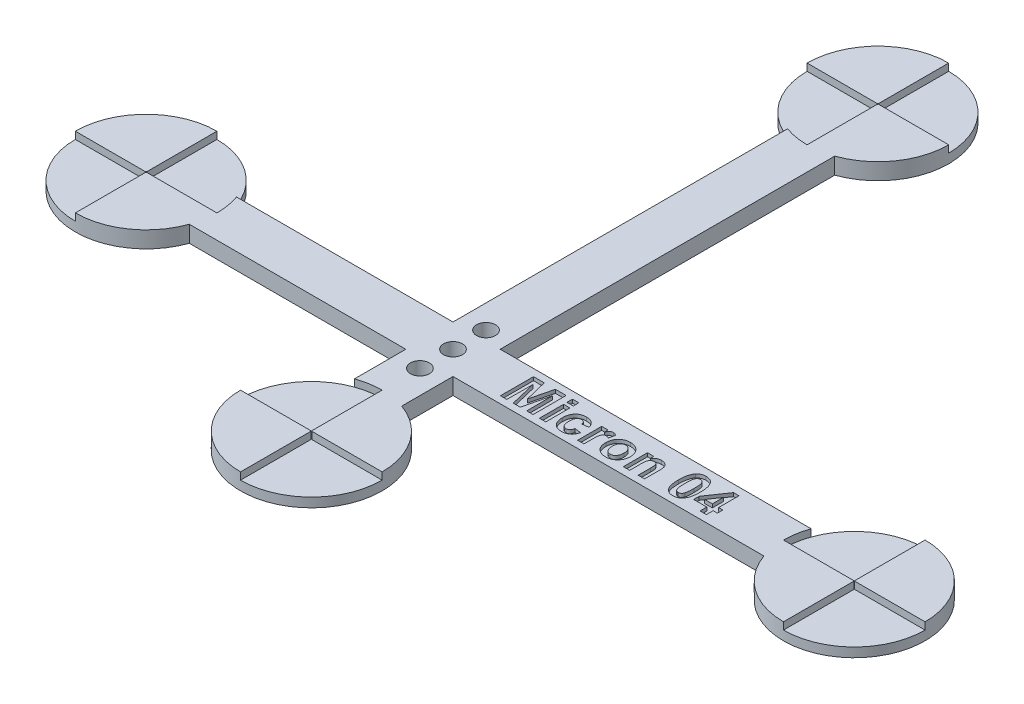
SolidWorks part; units mm, degrees
ref_plane "Front Plane" through (0, 0, 0) normal (0, 0, 1) x (1, 0, 0)
ref_plane "Top Plane" through (0, 0, 0) normal (0, 1, 0) x (1, 0, 0)
ref_plane "Right Plane" through (0, 0, 0) normal (1, 0, 0) x (0, 0, -1)
sketch "Sketch1" plane through (0, 0, 0) normal (0, 1, 0) x (1, 0, 0)
  line L0 (0, 0) -> (150, 0) construction
  line L1 (65, 90) -> (65, -30) construction
  line L2 (60, 75.8579) -> (60, 5)
  line L3 (70, 75.8579) -> (70, 5)
  line L4 (14.1421, 5) -> (60, 5)
  line L5 (14.1421, -5) -> (60, -5)
  line L6 (70, 5) -> (135.8579, 5)
  line L7 (60, -5) -> (60, -15.8579)
  line L8 (70, -5) -> (135.8579, -5)
  line L9 (70, -5) -> (70, -15.8579)
  arc A0 (14.1421, 5) -> (14.1421, -5) centre (0, 0) ccw
  arc A1 (135.8579, -5) -> (135.8579, 5) centre (150, 0) ccw
  arc A2 (70, 75.8579) -> (60, 75.8579) centre (65, 90) ccw
  arc A3 (60, -15.8579) -> (70, -15.8579) centre (65, -30) ccw
  point P15 (0, 0)
  point P16 (0, 0)
  point P19 (0, 0)
  point P20 (0, 0)
  dimension "D1" = 30
  dimension "D3" = 30
  dimension "D5" = 30
  dimension "D6" = 30
  dimension "D2" = 150
  dimension "D4" = 65
  dimension "D7" = 90
  dimension "D8" = 120
  dimension "D9" = 5
  dimension "D10" = 5
  dimension "D11" = 5
  dimension "D12" = 5
extrude "Boss-Extrude1" add sketch "Sketch1" along normal blind 3.5
sketch "Sketch2" plane through (0, 3.5, 0) normal (0, 1, 0) x (1, 0, 0)
  line L0 (65, -45) -> (65, -30.1)
  line L1 (-15, 0) -> (-0.1, 0)
  line L2 (50, 90) -> (64.9, 90)
  line L3 (0, 15) -> (0, 0.1)
  line L4 (150, 15) -> (150, 0.1)
  line L5 (50, -30) -> (64.9, -30)
  line L6 (65.1, 90) -> (80, 90)
  line L7 (65, 90.1) -> (65, 105)
  line L8 (65, 75) -> (65, 89.9)
  line L9 (65, -29.9) -> (65, -15)
  line L10 (65.1, -30) -> (80, -30)
  line L11 (135, 0) -> (149.9, 0)
  line L12 (0.1, 0) -> (15, 0)
  line L13 (0, -0.1) -> (0, -15)
  line L14 (150, -0.1) -> (150, -15)
  line L15 (150.1, 0) -> (165, 0)
  arc A0 (15, 0) -> (0, 15) centre (0, 0) ccw
  arc A1 (150, -15) -> (165, 0) centre (150, 0) ccw
  arc A2 (50, 90) -> (65, 75) centre (65, 90) ccw
  arc A3 (65, -15) -> (50, -30) centre (65, -30) ccw
  arc A4 (0, 0.1) -> (-0.1, 0) centre (0, 0) ccw
  arc A5 (65, 89.9) -> (65.1, 90) centre (65, 90) ccw
  arc A6 (149.9, 0) -> (150, -0.1) centre (150, 0) ccw
  arc A7 (64.9, -30) -> (65, -30.1) centre (65, -30) ccw
  arc A8 (65, 90.1) -> (64.9, 90) centre (65, 90) ccw
  arc A9 (80, 90) -> (65, 105) centre (65, 90) ccw
  arc A10 (65, -45) -> (80, -30) centre (65, -30) ccw
  arc A11 (65.1, -30) -> (65, -29.9) centre (65, -30) ccw
  arc A12 (-15, 0) -> (0, -15) centre (0, 0) ccw
  arc A13 (0, -0.1) -> (0.1, 0) centre (0, 0) ccw
  arc A14 (150.1, 0) -> (150, 0.1) centre (150, 0) ccw
  arc A15 (150, 15) -> (135, 0) centre (150, 0) ccw
  arc A16 (60, -15.8579) -> (70, -15.8579) centre (65, -30) ccw construction
  arc A17 (70, 75.8579) -> (60, 75.8579) centre (65, 90) ccw construction
  dimension "D1" = 0.2
  dimension "D2" = 0.2
  dimension "D3" = 0.2
  dimension "D4" = 0.2
extrude "Cut-Extrude1" cut sketch "Sketch2" against normal blind 1.52
sketch "Sketch3" plane through (0, 3.5, 0) normal (0, 1, 0) x (1, 0, 0)
  line L0 (65, -29.9) -> (65, -15) construction
  line L1 (65, 7) -> (65, -7) construction
  circle A0 centre (65, 0) radius 2
  circle A1 centre (65, 7) radius 2
  circle A2 centre (65, -7) radius 2
  point P2 (65, 0)
  dimension "D2" = 4
  dimension "D3" = 4
  dimension "D4" = 4
  dimension "D1" = 14
extrude "Cut-Extrude2" cut sketch "Sketch3" against normal through all
sketch "Sketch5" plane through (0, 3.5, 0) normal (0, 1, 0) x (1, 0, 0)
  line L0 (77.9289, -3.5) -> (127.9289, -3.5) construction
  line L1 (70, -5) -> (135.8579, -5) construction
  text T0 "Micron 04" font "Arial" height 7
  point P4 (102.9289, -3.5)
  point P5 (102.9289, -5)
  dimension "D1" = 1.5
  dimension "D2" = 50
extrude "Cut-Extrude3" cut sketch "Sketch5" against normal blind 0.75
